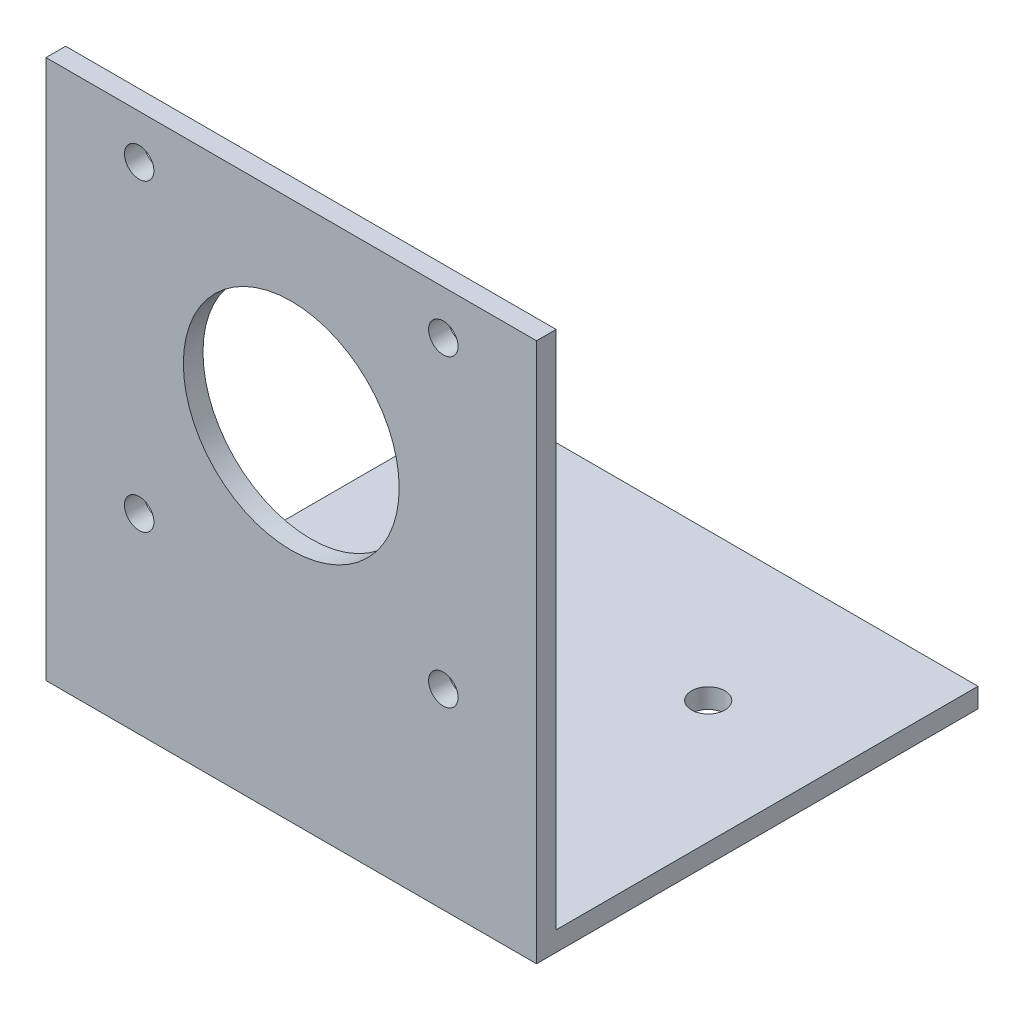
SolidWorks part; units mm, degrees
ref_plane "Front Plane" through (0, 0, 0) normal (0, 0, 1) x (1, 0, 0)
ref_plane "Top Plane" through (0, 0, 0) normal (0, 1, 0) x (1, 0, 0)
ref_plane "Right Plane" through (0, 0, 0) normal (1, 0, 0) x (0, 0, -1)
sketch "Sketch1" plane through (0, 0, 0) normal (0, 0, 1) x (1, 0, 0)
  line L1 (-25, 0) -> (25, 0)
  line L2 (-25, 0) -> (-25, 55)
  line L3 (-25, 55) -> (25, 55)
  line L4 (25, 0) -> (25, 55)
  dimension "D1" = 25
  dimension "D2" = 25
  dimension "D3" = 55
extrude "Boss-Extrude1" add sketch "Sketch1" against normal blind 2
sketch "Sketch2" plane through (0, 0, 0) normal (0, 0, 1) x (1, 0, 0)
  line L1 (-25, 0) -> (25, 0)
  line L2 (-25, 0) -> (-25, 2)
  line L3 (-25, 2) -> (25, 2)
  line L4 (25, 0) -> (25, 2)
  dimension "D1" = 25
  dimension "D2" = 25
  dimension "D3" = 2
extrude "Boss-Extrude2" add sketch "Sketch2" against normal blind 45
sketch "Sketch3" plane through (0, 0, 0) normal (0, 0, 1) x (1, 0, 0)
  circle A0 centre (-15.5, 19.5) radius 1.5
  circle A1 centre (-15.5, 50.5) radius 1.5
  circle A2 centre (15.5, 19.5) radius 1.5
  circle A3 centre (15.5, 50.5) radius 1.5
  dimension "D1" = 3
  dimension "D2" = 15.5
  dimension "D3" = 15.5
  dimension "D4" = 19.5
  dimension "D5" = 50.5
extrude "Cut-Extrude1" cut sketch "Sketch3" along normal through all and the other way through all
sketch "Sketch4" plane through (0, 0, 0) normal (0, 0, 1) x (1, 0, 0)
  circle A0 centre (0, 35) radius 11
  dimension "D1" = 22
  dimension "D2" = 35
extrude "Lo_tam_D22" cut sketch "Sketch4" along normal through all and the other way through all
sketch "Sketch5" plane through (0, 0, 0) normal (0, 1, 0) x (1, 0, 0)
  circle A0 centre (-12.5, 30) radius 1.7
  circle A1 centre (12.5, 30) radius 1.7
  dimension "D1" = 3.4
  dimension "D2" = 12.5
  dimension "D3" = 12.5
  dimension "D4" = 30
extrude "Hai_lo_chan_M3" cut sketch "Sketch5" along normal through all and the other way through all
